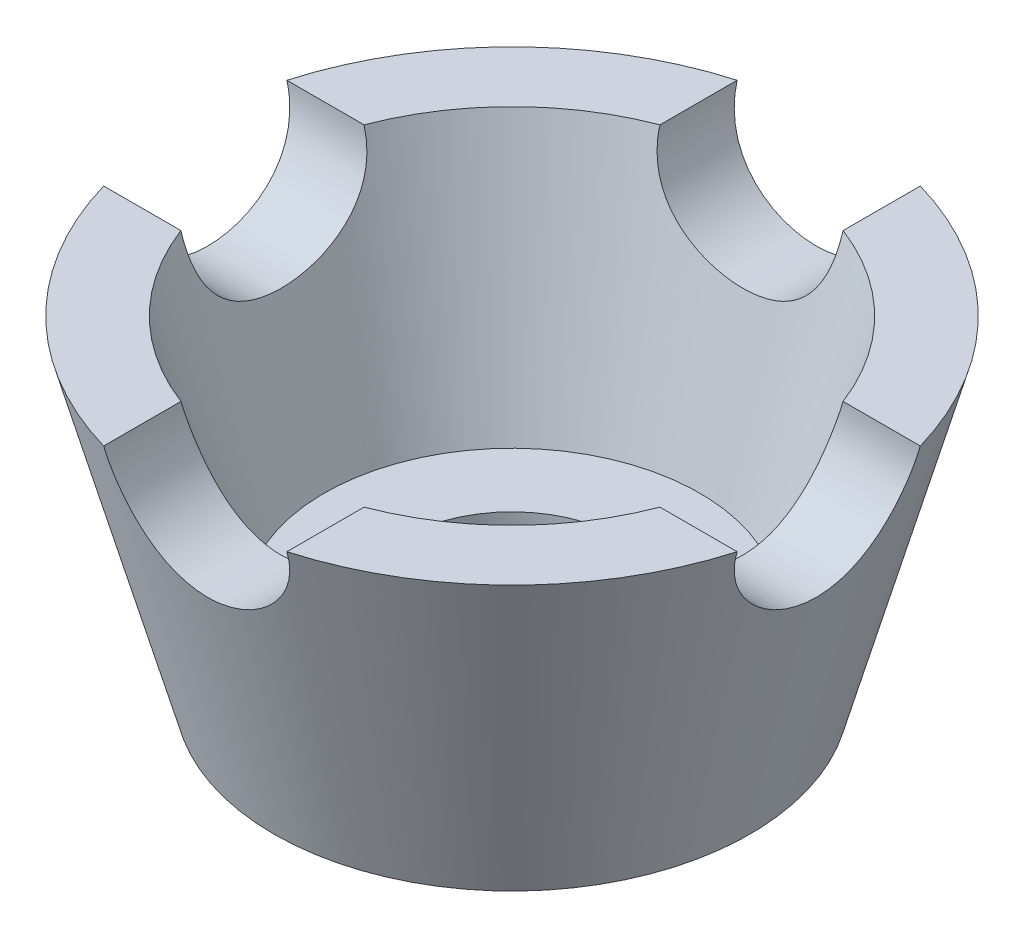
SolidWorks part; units mm, degrees
ref_plane "Front Plane" through (0, 0, 0) normal (0, 0, 1) x (1, 0, 0)
ref_plane "Top Plane" through (0, 0, 0) normal (0, 1, 0) x (1, 0, 0)
ref_plane "Right Plane" through (0, 0, 0) normal (1, 0, 0) x (0, 0, -1)
sketch "Sketch1" plane through (0, 0, 0) normal (0, 0, 1) x (1, 0, 0)
  line L0 (0, 54.7368) -> (0, -36.9474) construction
  line L1 (12, 0) -> (26, 0)
  line L2 (26, 0) -> (36, 36)
  line L3 (36, 36) -> (28, 36)
  line L4 (28, 36) -> (20.5, 9)
  line L5 (20.5, 9) -> (12, 9)
  line L6 (12, 9) -> (12, 0)
  dimension "D1" = 52
  dimension "D2" = 72
  dimension "D3" = 9
  dimension "D4" = 36
  dimension "D5" = 24
  dimension "D6" = 41
revolve "Revolve1" add sketch "Sketch1" angle 360 about L0
sketch "Sketch2" plane through (0, 0, 0) normal (1, 0, 0) x (0, 0, -1)
  line L0 (0, -2.9567) -> (0, 39.3613) construction
  line L1 (36, 36) -> (-36, 36) construction
  line L2 (-10, 36) -> (10, 36)
  arc A0 (-10, 36) -> (10, 36) centre (0, 36) ccw
  dimension "D1" = 10
extrude "Cut-Extrude1" cut sketch "Sketch2" against normal through all both and the other way through all
sketch "Sketch3" plane through (0, 0, 0) normal (0, 0, 1) x (1, 0, 0)
  line L0 (34.5832, 36) -> (-34.5832, 36) construction
  line L1 (-10, 36) -> (10, 36)
  arc A0 (-10, 36) -> (10, 36) centre (0, 36) ccw
  dimension "D1" = 10
extrude "Cut-Extrude2" cut sketch "Sketch3" against normal through all both and the other way through all
